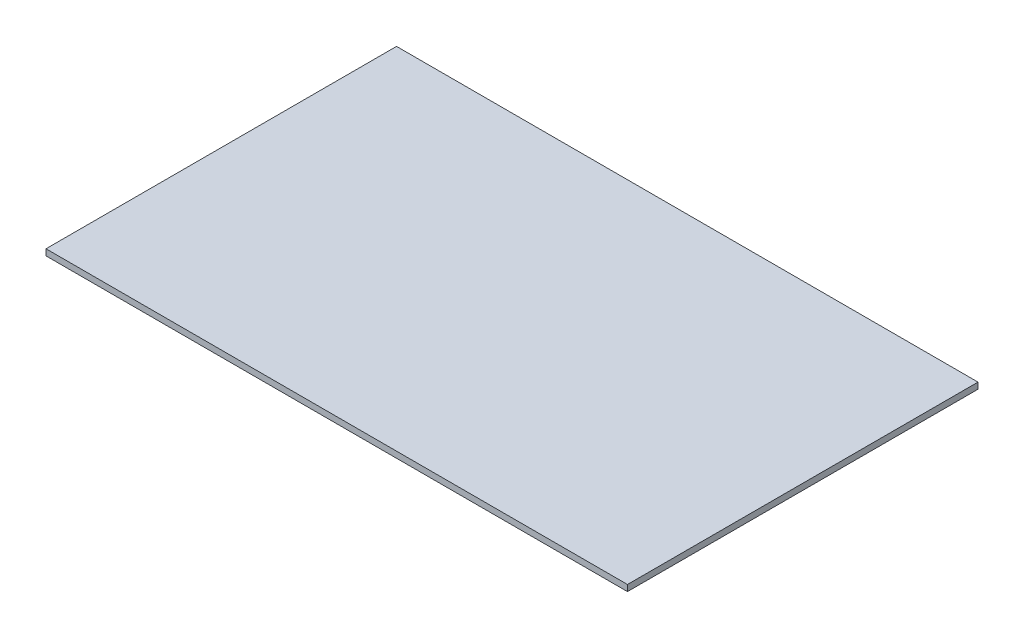
SolidWorks part; units mm, degrees
ref_plane "Front" through (0, 0, 0) normal (0, 0, 1) x (1, 0, 0)
ref_plane "Top" through (0, 0, 0) normal (0, 1, 0) x (1, 0, 0)
ref_plane "Right" through (0, 0, 0) normal (1, 0, 0) x (0, 0, -1)
sketch "Sketch1" plane through (0, 0, 0) normal (0, 1, 0) x (1, 0, 0)
  line L1 (141, -85) -> (-141, -85)
  line L2 (141, -85) -> (141, 85)
  line L3 (141, 85) -> (-141, 85)
  line L4 (-141, -85) -> (-141, 85)
  line L5 (141, -85) -> (-141, 85) construction
  line L6 (141, 85) -> (-141, -85) construction
  point P0 (0, 0)
  dimension "D1" = 170
  dimension "D2" = 282
extrude "Boss-Extrude1" add sketch "Sketch1" along normal mid plane 3
